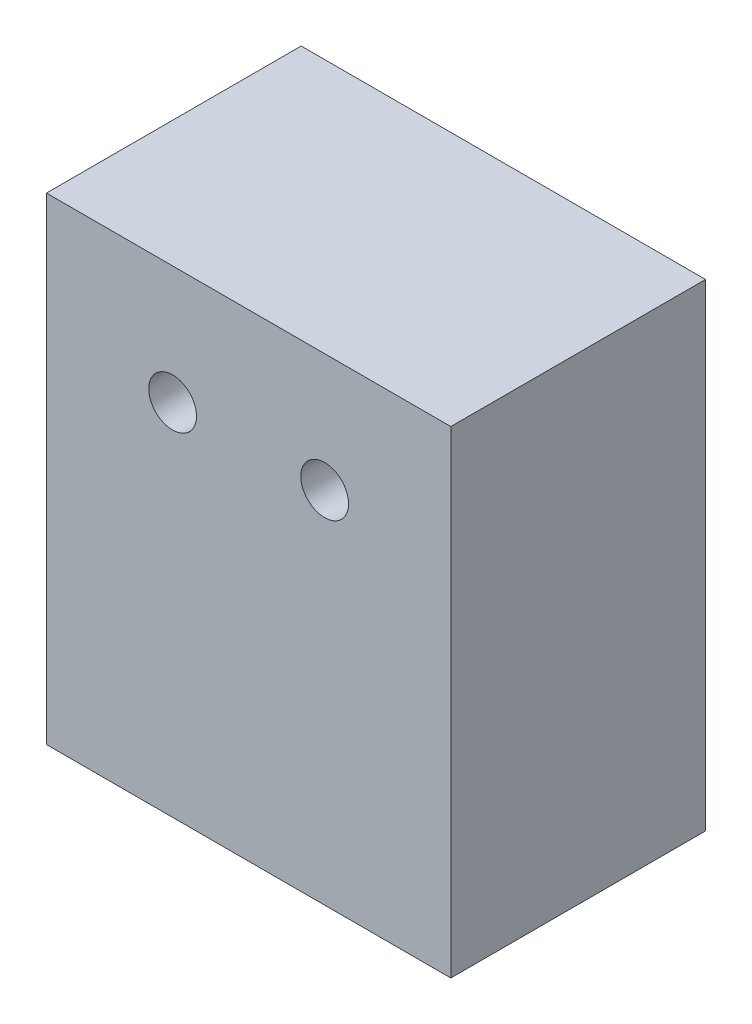
SolidWorks part; units mm, degrees
material "6061 Сплав"
ref_plane "Front" through (0, 0, 0) normal (0, 0, 1) x (1, 0, 0)
ref_plane "Top" through (0, 0, 0) normal (0, 1, 0) x (1, 0, 0)
ref_plane "Right" through (0, 0, 0) normal (1, 0, 0) x (0, 0, -1)
sketch "Эскиз1" plane through (0, 0, 0) normal (0, 0, 1) x (1, 0, 0)
  line L1 (-6.35, 7.5) -> (6.35, 7.5)
  line L2 (-6.35, 7.5) -> (-6.35, -7.5)
  line L3 (-6.35, -7.5) -> (6.35, -7.5)
  line L4 (6.35, 7.5) -> (6.35, -7.5)
  line L5 (-6.35, 7.5) -> (6.35, -7.5) construction
  line L6 (-6.35, -7.5) -> (6.35, 7.5) construction
  point P0 (0, 0)
  dimension "D1" = 15
  dimension "D2" = 12.7
extrude "Бобышка-Вытянуть1" add sketch "Эскиз1" along normal blind 8
sketch "Эскиз2" plane through (0, 0, 8) normal (0, 0, 1) x (1, 0, 0)
  line L0 (-6.35, -7.5) -> (6.35, -7.5) construction
  line L1 (-6.35, 7.5) -> (-6.35, -7.5) construction
  circle A0 centre (-2.3876, 3.786) radius 0.75
  circle A1 centre (2.3876, 3.79) radius 0.75
  dimension "D1" = 11.286
  dimension "D2" = 11.29
  dimension "D3" = 4.7752
  dimension "D4" = 3.9624
extrude "Вырез-Вытянуть1" cut sketch "Эскиз2" against normal blind 8
sketch "Эскиз3" plane through (0, -7.5, 0) normal (0, -1, 0) x (1, 0, 0)
  line L0 (-6.35, 8) -> (-6.35, 0) construction
  line L1 (-6.35, 8) -> (6.35, 8) construction
  circle A0 centre (-2.5, 4) radius 1.25
  circle A1 centre (2.5, 4) radius 1.25
  dimension "D1" = 5
  dimension "D2" = 3.85
  dimension "D3" = 4
  dimension "D4" = 4
extrude "Вырез-Вытянуть2" cut sketch "Эскиз3" against normal blind 5
